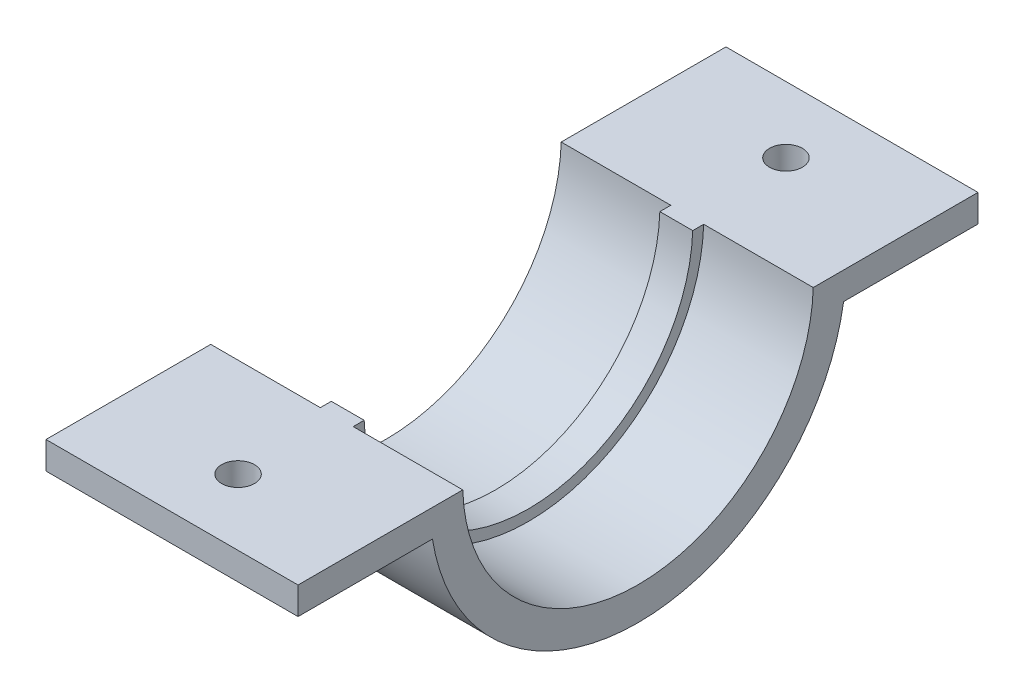
SolidWorks part; units mm, degrees
ref_plane "Front Plane" through (0, 0, 0) normal (0, 0, 1) x (1, 0, 0)
ref_plane "Top Plane" through (0, 0, 0) normal (0, 1, 0) x (1, 0, 0)
ref_plane "Right Plane" through (0, 0, 0) normal (1, 0, 0) x (0, 0, -1)
sketch "Sketch2" plane through (0, 0, 0) normal (0, 1, 0) x (1, 0, 0)
  line L0 (-71.7222, 0) -> (83.9696, 0) construction
  line L1 (-11.5, 16) -> (-1.5, 16)
  line L2 (-1.5, 16) -> (-1.5, 15)
  line L3 (-1.5, 15) -> (1.5, 15)
  line L4 (0, 51.3789) -> (0, -38.4859) construction
  line L5 (-11.5, 16) -> (-11.5, 19)
  line L6 (-11.5, 19) -> (11.5, 19)
  line L7 (11.5, 16) -> (11.5, 19)
  line L8 (1.5, 16) -> (1.5, 15)
  line L9 (11.5, 16) -> (1.5, 16)
  point P12 (0, 19)
  point P14 (0, 15)
  dimension "D1" = 16
  dimension "D2" = 15
  dimension "D3" = 1.5
  dimension "D4" = 10
  dimension "D5" = 3
revolve "Revolve1" add sketch "Sketch2" angle 360 about L0
sketch "Sketch3" plane through (0, 0, 0) normal (1, 0, 0) x (0, 0, -1)
  line L0 (-38.0691, 0) -> (35.3359, 0) construction
  line L1 (0, 27.1286) -> (0, -26.0041) construction
  line L2 (17.4601, -3) -> (31.0263, -3)
  line L3 (-17.4601, 3) -> (-31.0263, 3)
  line L4 (-17.4601, 3) -> (-17.4601, -3)
  line L5 (-17.4601, -3) -> (-31.0263, -3)
  line L6 (-31.0263, 3) -> (-31.0263, -3)
  line L7 (31.0263, 3) -> (31.0263, -3)
  line L8 (17.4601, 3) -> (31.0263, 3)
  line L9 (17.4601, 3) -> (17.4601, -3)
  dimension "D1" = 6
extrude "Boss-Extrude1" add sketch "Sketch3" along normal mid plane 23
sketch "Sketch4" plane through (0, 0, 0) normal (0, 1, 0) x (1, 0, 0)
  line L0 (-34.5056, 0) -> (37.3088, 0) construction
  circle A0 centre (0, 25) radius 1.5
  circle A1 centre (0, -25) radius 1.5
  dimension "D1" = 3
  dimension "D2" = 25
extrude "Cut-Extrude1" cut sketch "Sketch4" against normal mid plane 23
sketch "Sketch5" plane through (0, 0, 0) normal (1, 0, 0) x (0, 0, -1)
  line L0 (-44.9576, 0) -> (42.9868, 0) construction
  line L2 (-37.8752, -0.5) -> (37.8752, -0.5)
  line L3 (-37.8752, -0.5) -> (-37.8752, 0.5)
  line L4 (-37.8752, 0.5) -> (37.8752, 0.5)
  line L5 (37.8752, -0.5) -> (37.8752, 0.5)
  line L6 (-37.8752, -0.5) -> (37.8752, 0.5) construction
  line L7 (-37.8752, 0.5) -> (37.8752, -0.5) construction
  point P3 (0, 0)
  dimension "D1" = 1
extrude "Cut-Extrude2" cut sketch "Sketch5" against normal mid plane 52
delete or keep bodies "Body-Delete/Keep 2" type delete bodies bodies 105
